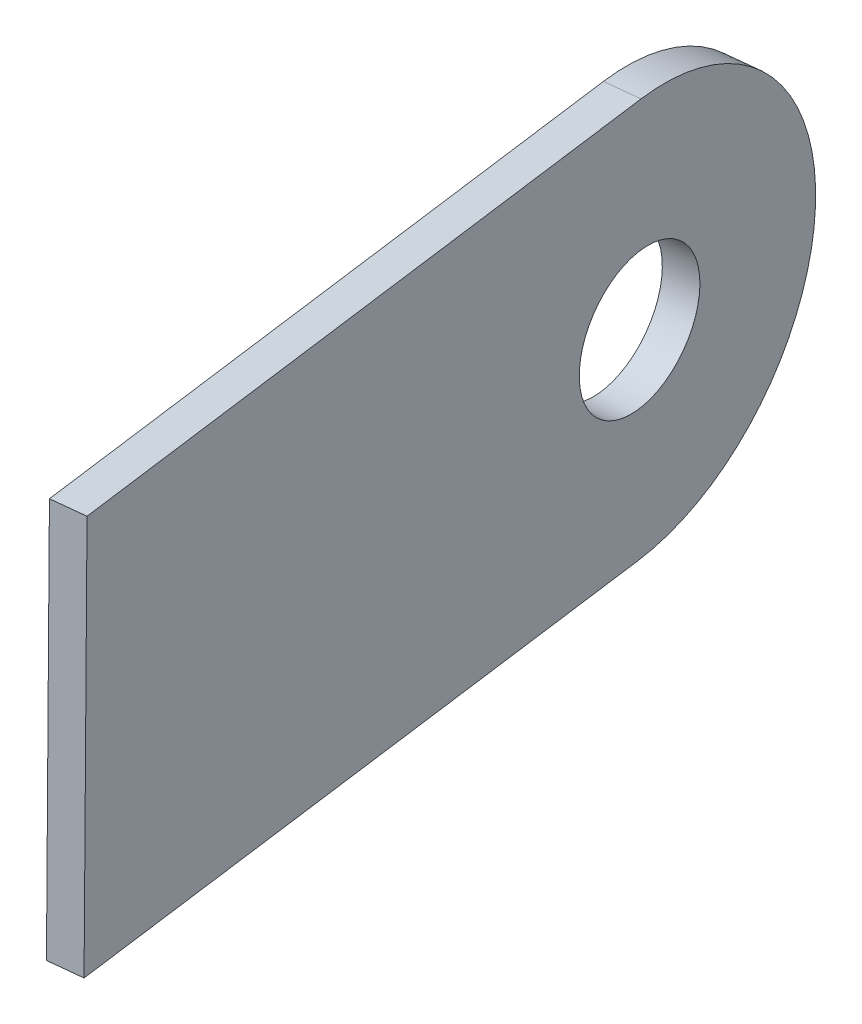
SolidWorks part; units mm, degrees
ref_plane "Front Plane" through (0, 0, 0) normal (0, 0, 1) x (1, 0, 0)
ref_plane "Top Plane" through (0, 0, 0) normal (0, 1, 0) x (1, 0, 0)
ref_plane "Right Plane" through (0, 0, 0) normal (1, 0, 0) x (0, 0, -1)
sketch "Sketch2" plane through (368.9369, -5.3839, -45.5872) normal (0.9923, -0.0145, -0.1226) x (-0.1226, 0.0018, -0.9925)
  line L0 (479.6086, 148.8821) -> (509.5795, 149.1312)
  line L1 (478.9871, 223.6738) -> (480.2153, 75.8596) construction
  line L2 (509.7378, 130.0818) -> (479.7669, 129.8328)
  line L3 (479.7669, 129.8328) -> (479.6086, 148.8821)
  circle A0 centre (509.6587, 139.6065) radius 3.2639
  arc A1 (509.5795, 149.1312) -> (509.7378, 130.0818) centre (509.6587, 139.6065) cw
  point P9 (510.13, 138.7891)
  dimension "D1" = 6.5278
  dimension "D2" = 19.05
extrude "Boss-Extrude1" add sketch "Sketch2" along normal blind 1.5875
